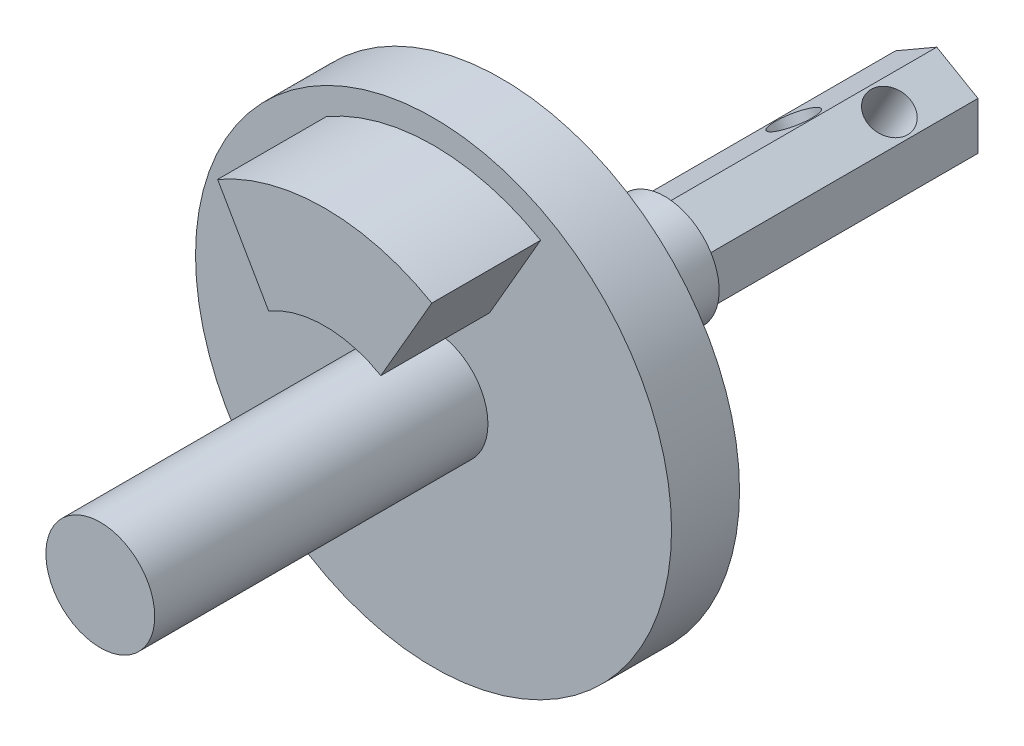
SolidWorks part; units mm, degrees
ref_plane "Front Plane" through (0, 0, 0) normal (0, 0, 1) x (1, 0, 0)
ref_plane "Top Plane" through (0, 0, 0) normal (0, 1, 0) x (1, 0, 0)
ref_plane "Right Plane" through (0, 0, 0) normal (1, 0, 0) x (0, 0, -1)
sketch "Sketch1" plane through (0, 0, 0) normal (0, 0, 1) x (1, 0, 0)
  circle A0 centre (0, 0) radius 17.5
  dimension "D1" = 35
extrude "Boss-Extrude1" add sketch "Sketch1" along normal mid plane 5
sketch "Sketch2" plane through (0, 0, 2.5) normal (0, 0, 1) x (1, 0, 0)
  line L3 (0, 0) -> (0, 11) construction
  line L4 (7.875, 13.6399) -> (4.125, 7.1447)
  line L5 (-4.125, 7.1447) -> (-7.875, 13.6399)
  arc A1 (4.125, 7.1447) -> (-4.125, 7.1447) centre (0, 0) ccw
  arc A6 (-7.875, 13.6399) -> (7.875, 13.6399) centre (0, 0) cw
  circle A7 centre (0, 0) radius 17.5 construction
  dimension "D2" = 7.5
  dimension "D3" = 1.75
  dimension "D1" = 30
extrude "Boss-Extrude2" add sketch "Sketch2" along normal blind 8
sketch "Sketch3" plane through (0, 0, 2.5) normal (0, 0, 1) x (1, 0, 0)
  circle A0 centre (0, 0) radius 4
extrude "Boss-Extrude3" add sketch "Sketch3" along normal blind 24.5
sketch "Sketch7" plane through (0, 0, -2.5) normal (0, 0, -1) x (-1, 0, 0)
  circle A0 centre (0, 0) radius 4
extrude "Boss-Extrude4" add sketch "Sketch7" along normal blind 12
sketch "Sketch9" plane through (0, 0, -14.5) normal (0, 0, -1) x (-1, 0, 0)
  line L11 (0, 3.5) -> (-3.0311, 1.75)
  line L12 (-3.0311, 1.75) -> (-3.0311, -1.75)
  line L13 (-3.0311, -1.75) -> (0, -3.5)
  line L14 (0, -3.5) -> (3.0311, -1.75)
  line L15 (3.0311, -1.75) -> (3.0311, 1.75)
  line L16 (3.0311, 1.75) -> (0, 3.5)
  point P5 (0, 0)
  point P6 (0, 0)
  point P8 (0, 0)
  point P11 (0, 0)
  point P13 (0, 0)
  point P15 (0, 0)
extrude "Boss-Extrude5" add sketch "Sketch9" along normal blind 20
sketch "Sketch10" plane through (-1.5155, -2.625, 0) normal (-0.5, -0.866, 0) x (0.866, -0.5, 0)
  line L0 (0, -34.5) -> (0, -29.5) construction
  line L1 (1.75, -34.5) -> (-1.75, -34.5) construction
  circle A0 centre (0, -29.5) radius 1.55
extrude "Cut-Extrude1" cut sketch "Sketch10" against normal blind 6.1
sketch "Sketch11" plane through (1.5155, -2.625, 0) normal (-0.5, 0.866, 0) x (0, 0, 1)
  line L0 (-34.5, 0) -> (-25.5, 0) construction
  line L3 (-34.5, -1.75) -> (-34.5, 1.75) construction
  circle A1 centre (-25.5, 0) radius 1.55
  point P4 (0, 0)
  point P6 (0, 0)
extrude "Cut-Extrude4" cut sketch "Sketch11" along normal blind 6.1
